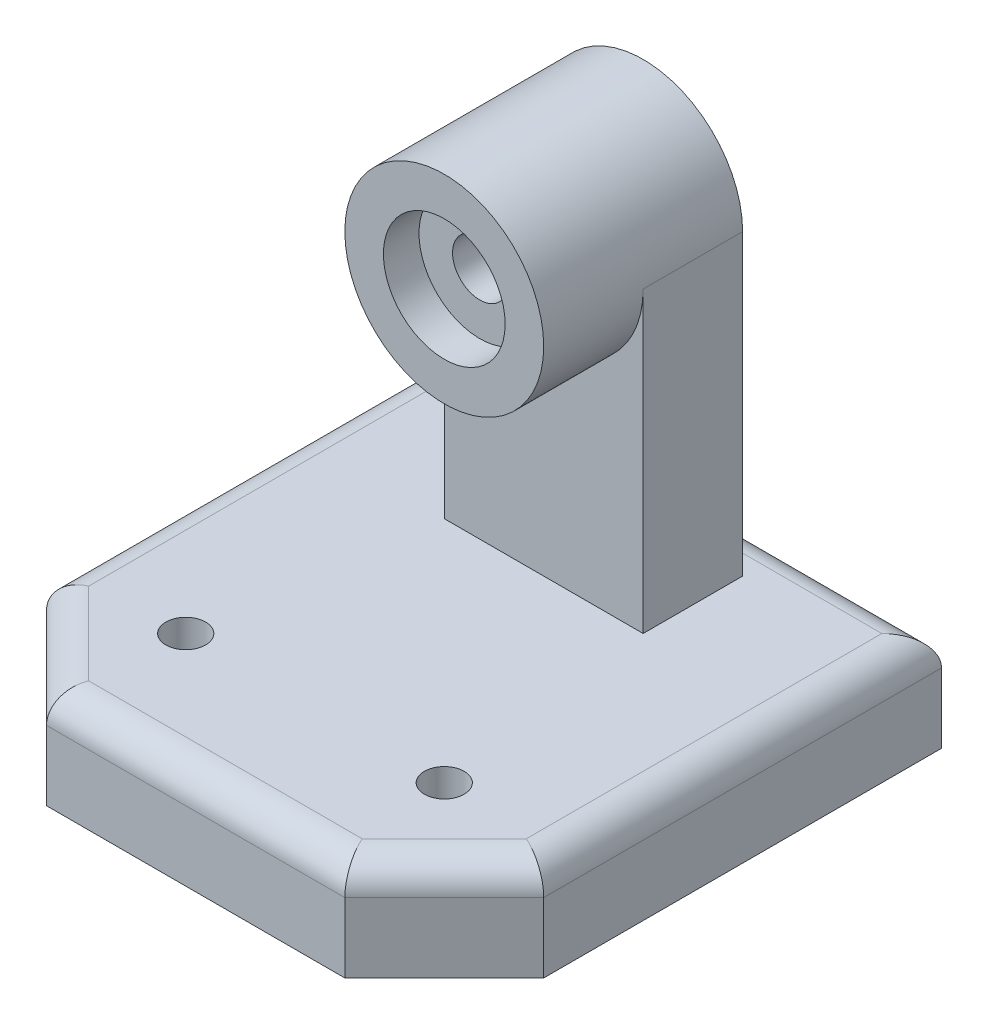
SolidWorks part; units mm, degrees
material "Nylon 101"
ref_plane "Front Plane" through (0, 0, 0) normal (0, 0, 1) x (1, 0, 0)
ref_plane "Top Plane" through (0, 0, 0) normal (0, 1, 0) x (1, 0, 0)
ref_plane "Right Plane" through (0, 0, 0) normal (1, 0, 0) x (0, 0, -1)
sketch "Sketch1" plane through (0, 0, 0) normal (0, 1, 0) x (1, 0, 0)
  line L1 (0, 0) -> (50, 0)
  line L2 (0, 0) -> (0, -50)
  line L3 (0, -50) -> (50, -50)
  line L4 (50, 0) -> (50, -50)
  dimension "D1" = 50
  dimension "D2" = 50
extrude "Boss-Extrude1" add sketch "Sketch1" along normal blind 10
sketch "Sketch2" plane through (0, 10, 0) normal (0, 1, 0) x (1, 0, 0)
  line L0 (50, 0) -> (0, 0) construction
  line L1 (15, -5) -> (35, -5)
  line L2 (15, -5) -> (15, -15)
  line L3 (15, -15) -> (35, -15)
  line L4 (35, -5) -> (35, -15)
  point P6 (25, -5)
  point P7 (25, 0)
  dimension "D1" = 20
  dimension "D2" = 10
  dimension "D3" = 5
extrude "Boss-Extrude2" add sketch "Sketch2" along normal blind 30
sketch "Sketch3" plane through (0, 0, 5) normal (0, 0, -1) x (-1, 0, 0)
  line L0 (-35, 40) -> (-15, 40) construction
  circle A0 centre (-25, 40) radius 10
  dimension "D1" = 20
extrude "Boss-Extrude3" add sketch "Sketch3" against normal blind 20
hole_wizard "CBORE for M5 Hex Head Bolt1" positions "Sketch4" profile "Sketch5" counterbore size "M5" standard "ANSI Metric" end condition through all
sketch "Sketch4" plane through (0, 0, 25) normal (0, 0, 1) x (1, 0, 0)
  point P0 (25, 40)
sketch "Sketch5" plane through (25, 40, 25) normal (1, 0, 0) x (0, -1, 0)
  line L0 (0, 0) -> (0, 25)
  line L1 (0, 25) -> (2.75, 25)
  line L3 (2.75, 25) -> (2.75, 3.58)
  line L4 (2.75, 3.58) -> (6.12, 3.58)
  line L5 (6.12, 3.58) -> (6.12, 0)
  line L7 (6.12, 0) -> (0, 0)
  line L11 (0, -6.35) -> (0, 107.95) construction
  dimension "Thru Hole Dia." = 5.5
  dimension "Thru Hole Depth" = 25
  dimension "C'Bore Dia." = 12.24
  dimension "C'Bore Depth" = 3.58
hole_wizard "Ø4.0mm Dowel Hole1" positions "Sketch6" profile "Sketch7" hole size "Ø4.0" standard "ANSI Metric" end condition through all
sketch "Sketch6" plane through (0, 10, 0) normal (0, 1, 0) x (1, 0, 0)
  line L0 (50, 0) -> (0, 0) construction
  line L1 (0, -50) -> (50, -50) construction
  point P0 (12, -38)
  point P2 (38, -38)
  point P9 (25, -50)
  dimension "D1" = 38
  dimension "D2" = 38
  dimension "D3" = 26
  dimension "D4" = 13
sketch "Sketch7" plane through (12, 10, 38) normal (1, 0, 0) x (0, 0, 1)
  line L0 (0, 0) -> (0, 10)
  line L1 (0, 10) -> (2, 10)
  line L2 (2, 10) -> (2, 0)
  line L5 (2, 0) -> (0, 0)
  line L11 (0, -6.35) -> (0, 107.95) construction
  dimension "Thru Hole Dia." = 4
  dimension "Thru Hole Depth" = 10
chamfer "Chamfer1" distance 10 angle 45 2 edges at (50, 5, 50) (0, 5, 50)
fillet "Fillet1" radius 3 6 edges at (25, 10, 0) (50, 10, 20) (45, 10, 45) (25, 10, 50) (5, 10, 45) (0, 10, 20)
